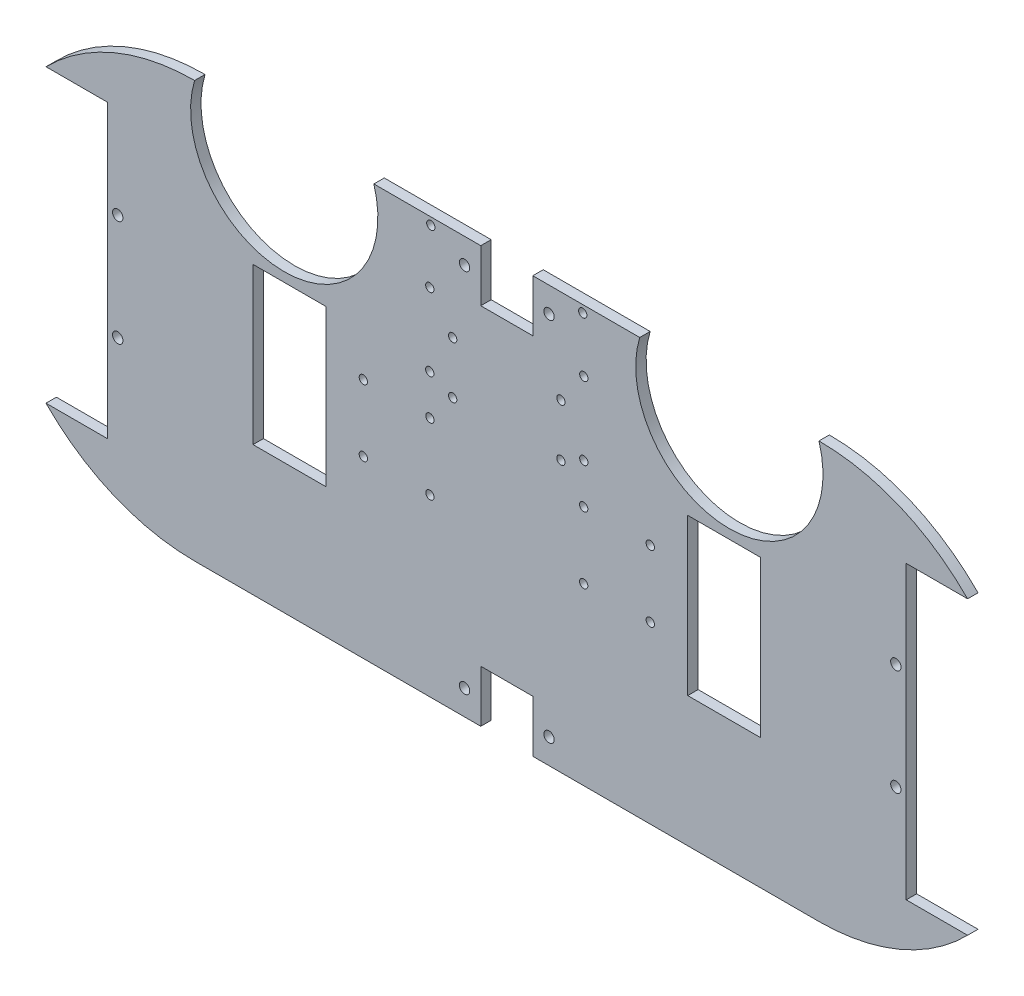
SolidWorks part; units mm, degrees
ref_plane "Front Plane" through (0, 0, 0) normal (0, 0, 1) x (1, 0, 0)
ref_plane "Top Plane" through (0, 0, 0) normal (0, 1, 0) x (1, 0, 0)
ref_plane "Right Plane" through (0, 0, 0) normal (1, 0, 0) x (0, 0, -1)
sketch "Sketch1" plane through (0, 0, 0) normal (0, 0, 1) x (1, 0, 0)
  line L0 (106.477, 150.6351) -> (77, 150.6351)
  line L1 (-264.9373, -19.3649) -> (35.0627, -19.3649)
  line L3 (-264.9373, 180.6351) -> (35.0627, 180.6351)
  line L5 (77, 150.6351) -> (77, 10.6351)
  line L6 (77, 10.6351) -> (106.477, 10.6351)
  line L8 (-306.8745, 10.6351) -> (-336.3515, 10.6351)
  line L9 (-306.8745, 150.6351) -> (-306.8745, 10.6351)
  line L10 (-336.3515, 150.6351) -> (-306.8745, 150.6351)
  arc A0 (35.0627, 180.6351) -> (35.0627, -19.3649) centre (35.0627, 80.6351) cw
  arc A1 (-264.9373, 180.6351) -> (-264.9373, -19.3649) centre (-264.9373, 80.6351) ccw
  circle A2 centre (-77.935, 116.0153) radius 2
  circle A3 centre (-151.935, 116.0153) radius 2
  arc A4 (35.0627, 180.6351) -> (-51.0614, 180.6351) centre (-7.9993, 167.5715) cw
  arc A8 (-264.9373, 180.6351) -> (-178.8131, 180.6351) centre (-221.8752, 167.5715) ccw
  circle A9 centre (-151.935, 151.0153) radius 2
  circle A10 centre (-77.935, 151.0153) radius 2
  circle A16 centre (-78.4363, 177.1351) radius 2
  circle A17 centre (-151.4363, 177.1351) radius 2
  circle A18 centre (-140.9363, 110.6351) radius 2
  circle A19 centre (-140.9363, 135.6351) radius 2
  circle A20 centre (-88.9363, 135.6351) radius 2
  circle A21 centre (-88.9363, 110.6351) radius 2
  point P0 (0, 0)
  point P2 (-364.9373, 80.6351)
  point P7 (135.0627, 80.6351)
  dimension "D2" = 100
  dimension "D3" = 180.6351
  dimension "D4" = 100
  dimension "D5" = 157.3021
  dimension "D6" = 373.7395
  dimension "D7" = 100
  dimension "D8" = 100
  dimension "D16" = 71.4143
  dimension "D17" = 4
  dimension "D15" = 30
  dimension "D18" = 135.3802
  dimension "D19" = 154.935
  dimension "D20" = 170.3802
  dimension "D21" = 228.9395
  dimension "D22" = 4
  dimension "D23" = 74
  dimension "D24" = 170.3802
  dimension "D25" = 154.9395
  dimension "D26" = 135.3802
  dimension "D27" = 45
  dimension "D28" = 84.9993
  dimension "D29" = 186.9364
  dimension "D30" = 97.0169
  dimension "D31" = 45
  dimension "D32" = 13.0636
  dimension "D33" = 84.9993
  dimension "D34" = 4
  dimension "D35" = 165.9382
  dimension "D36" = 70
  dimension "D37" = 25
  dimension "D38" = 10.9987
  dimension "D39" = 52
  dimension "D40" = 25
  dimension "D41" = 25
  dimension "D42" = 52
  dimension "D43" = 26.1198
  dimension "D44" = 73.4987
  dimension "D45" = 26.1198
  dimension "D46" = 73
  dimension "D47" = 4
  dimension "D1" = 200
  dimension "D9" = 30
  dimension "D10" = 30
  dimension "D11" = 77
  dimension "D12" = 270
  dimension "D13" = 383.8745
  dimension "D14" = 30
extrude "Boss-Extrude1" add sketch "Sketch1" against normal blind 5
sketch "Sketch2" plane through (0, 0, -5) normal (0, 0, -1) x (-1, 0, 0)
  line L5 (264.9373, -19.3649) -> (-35.0627, -19.3649) construction
  line L7 (114.9373, 180.6351) -> (114.9373, -19.3649) construction
  line L15 (306.8745, 150.6351) -> (306.8745, 10.6351) construction
  line L16 (201.8745, 118.1351) -> (236.8745, 118.1351)
  line L17 (201.8745, 118.1351) -> (201.8745, 43.1351)
  line L18 (201.8745, 43.1351) -> (236.8745, 43.1351)
  line L19 (236.8745, 118.1351) -> (236.8745, 43.1351)
  line L20 (264.9373, -19.3649) -> (-35.0627, -19.3649) construction
  line L21 (28, 118.1351) -> (-7, 118.1351)
  line L22 (28, 118.1351) -> (28, 43.1351)
  line L23 (28, 43.1351) -> (-7, 43.1351)
  line L24 (-7, 118.1351) -> (-7, 43.1351)
  line L26 (306.8745, 80.6351) -> (-77, 80.6351) construction
  line L27 (-77, 150.6351) -> (-77, 10.6351) construction
  circle A0 centre (301.8745, 106.1351) radius 2.5
  circle A1 centre (301.8745, 55.1351) radius 2.5
  circle A2 centre (-72, 55.1351) radius 2.5
  circle A3 centre (-72, 106.1351) radius 2.5
  dimension "D6" = 25.5
  dimension "D7" = 5
  dimension "D8" = 5
  dimension "D1" = 70
  dimension "D2" = 75
  dimension "D3" = 35
  dimension "D4" = 62.5
  dimension "D5" = 201.8745
extrude "Cut-Extrude1" cut sketch "Sketch2" against normal blind 10
sketch "Sketch4" plane through (0, 0, -5) normal (0, 0, -1) x (-1, 0, 0)
  line L0 (264.9373, -19.3649) -> (-35.0627, -19.3649) construction
  line L1 (-77, 150.6351) -> (-77, 10.6351) construction
  line L2 (178.8131, 180.6351) -> (51.0614, 180.6351) construction
  line L5 (114.9373, 180.6351) -> (114.9373, -19.3649) construction
  circle A0 centre (46, 64.6951) radius 2
  circle A1 centre (46, 96.6951) radius 2
  circle A2 centre (78, 64.6951) radius 2
  circle A3 centre (78, 96.6951) radius 2
  circle A4 centre (151.8745, 64.6951) radius 2
  circle A5 centre (183.8745, 64.6951) radius 2
  circle A6 centre (183.8745, 96.6951) radius 2
  circle A7 centre (151.8745, 96.6951) radius 2
  dimension "D1" = 84.06
  dimension "D2" = 123
  dimension "D3" = 4
  dimension "D4" = 83.94
  dimension "D6" = 4
  dimension "D7" = 155
  dimension "D8" = 155
  dimension "D9" = 83.94
  dimension "D11" = 200
  dimension "D5" = 123
  dimension "D10" = 84.06
extrude "Cut-Extrude3" cut sketch "Sketch4" against normal blind 10
sketch "Sketch5" plane through (0, 0, -5) normal (0, 0, -1) x (-1, 0, 0)
  line L0 (306.8745, 150.6351) -> (306.8745, 10.6351) construction
  line L1 (-77, 80.6351) -> (306.8745, 80.6351) construction
  line L2 (178.8131, 180.6351) -> (51.0614, 180.6351) construction
  line L3 (-77, 150.6351) -> (-77, 10.6351) construction
  circle A2 centre (94.6373, 168.6351) radius 2.5
  circle A3 centre (135.2373, 168.6351) radius 2.5
  circle A4 centre (-72, 106.1351) radius 2.5 construction
  circle A7 centre (94.6373, -7.3649) radius 2.5
  circle A8 centre (135.2373, -7.3649) radius 2.5
  dimension "D1" = 40.6
  dimension "D2" = 12
  dimension "D3" = 12
  dimension "D4" = 171.6373
  dimension "D5" = 171.6373
extrude "Cut-Extrude4" cut sketch "Sketch5" against normal blind 10
sketch "Sketch6" plane through (0, 0, -5) normal (0, 0, -1) x (-1, 0, 0)
  line L0 (264.9373, -19.3649) -> (-35.0627, -19.3649) construction
  line L1 (102.4395, -19.3649) -> (127.4395, -19.3649)
  line L2 (102.4395, -19.3649) -> (102.4395, 5.6351)
  line L3 (102.4395, 5.6351) -> (127.4395, 5.6351)
  line L4 (127.4395, -19.3649) -> (127.4395, 5.6351)
  line L5 (306.8745, 150.6351) -> (306.8745, 10.6351) construction
  line L6 (-77, 80.6351) -> (306.8745, 80.6351) construction
  line L7 (-77, 150.6351) -> (-77, 10.6351) construction
  line L8 (102.4395, 180.6351) -> (102.4395, 155.6351)
  line L9 (127.4395, 180.6351) -> (127.4395, 155.6351)
  line L10 (102.4395, 155.6351) -> (127.4395, 155.6351)
  line M38 (178.8131, 180.6351) -> (51.0614, 180.6351)
  line M45 (-35.0627, -19.3649) -> (264.9373, -19.3649)
  dimension "D1" = 25
  dimension "D2" = 25
  dimension "D3" = 179.435
extrude "Cut-Extrude5" cut sketch "Sketch6" against normal blind 10 contours L4 L3 L2 M45 | L8 L10 L9 M38
